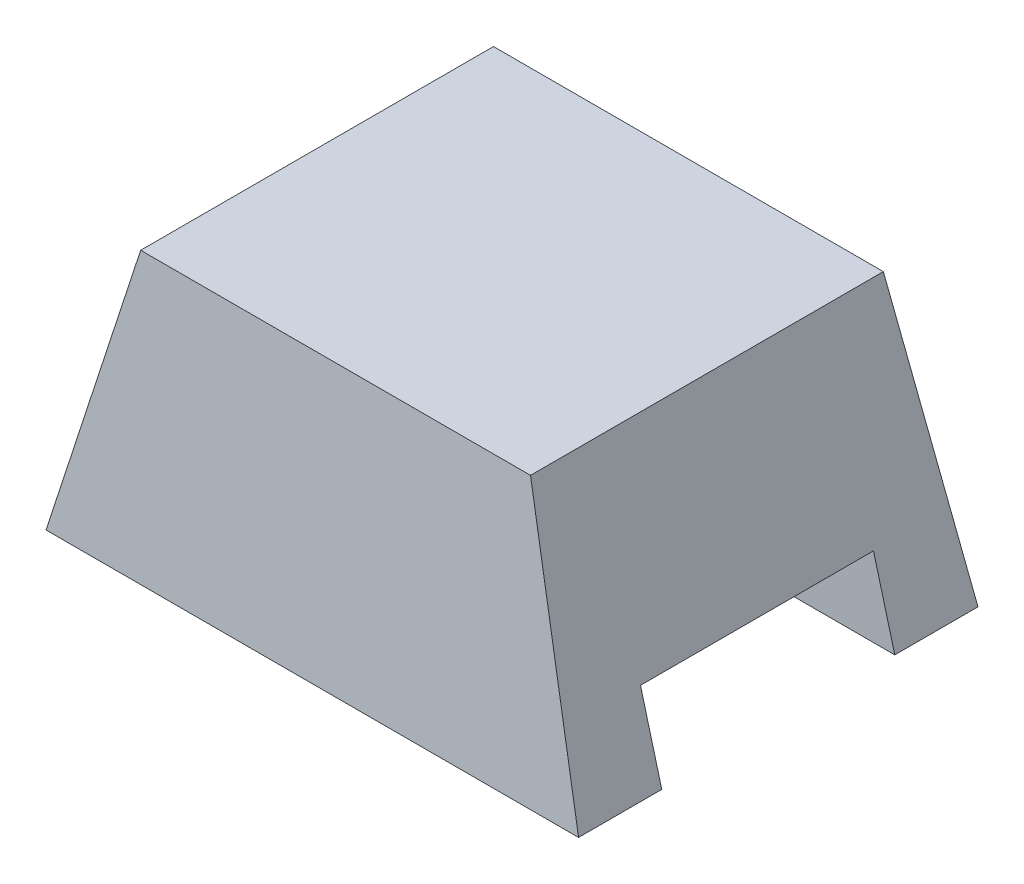
SolidWorks part; units mm, degrees
ref_plane "정면" through (0, 0, 0) normal (0, 0, 1) x (1, 0, 0)
ref_plane "윗면" through (0, 0, 0) normal (0, 1, 0) x (1, 0, 0)
ref_plane "우측면" through (0, 0, 0) normal (1, 0, 0) x (0, 0, -1)
sketch "스케치5" plane through (0, 0, 0) normal (0, 0, 1) x (1, 0, 0)
  line L0 (0, 0) -> (80, 0)
  line L1 (80, 0) -> (80, 40)
  line L2 (80, 40) -> (0, 40)
  line L3 (0, 40) -> (0, 0)
  dimension "D1" = 80
  dimension "D2" = 40
extrude "보스-돌출3" add sketch "스케치5" along normal blind 60 contours L2 L3 L0 L1
draft "구배6" type of draft neutral plane draft angle 15 faces to draft 2 face at (80, 20, 30) face at (0, 20, 30) neutral plane through (0, 0, 60) neutral plane normal (0, -1, 0) reverse direction yes parameters "D1"=15
draft "구배7" type of draft neutral plane draft angle 5 faces to draft 2 face at (40, 20, 0) face at (40, 20, 60) neutral plane through (0, 0, 60) neutral plane normal (0, -1, 0) reverse direction yes parameters "D1"=5
sketch "스케치8" plane through (0, 0, 0) normal (-0.9659, 0.2588, 0) x (0, 0, 1)
  line L0 (60, 0) -> (0, 0) construction
  line L1 (47.5, 0) -> (47.5, 31.411)
  line L2 (47.5, 31.411) -> (12.5, 31.411)
  line L3 (12.5, 31.411) -> (12.5, 0)
  line L4 (12.5, 0) -> (47.5, 0)
  line L5 (56.5005, 41.411) -> (3.4995, 41.411) construction
  dimension "D1" = 35
  dimension "D2" = 12.5
  dimension "D3" = 10
extrude "컷-돌출1" cut sketch "스케치8" against normal blind 117 contours L2 L3 L4 L1
